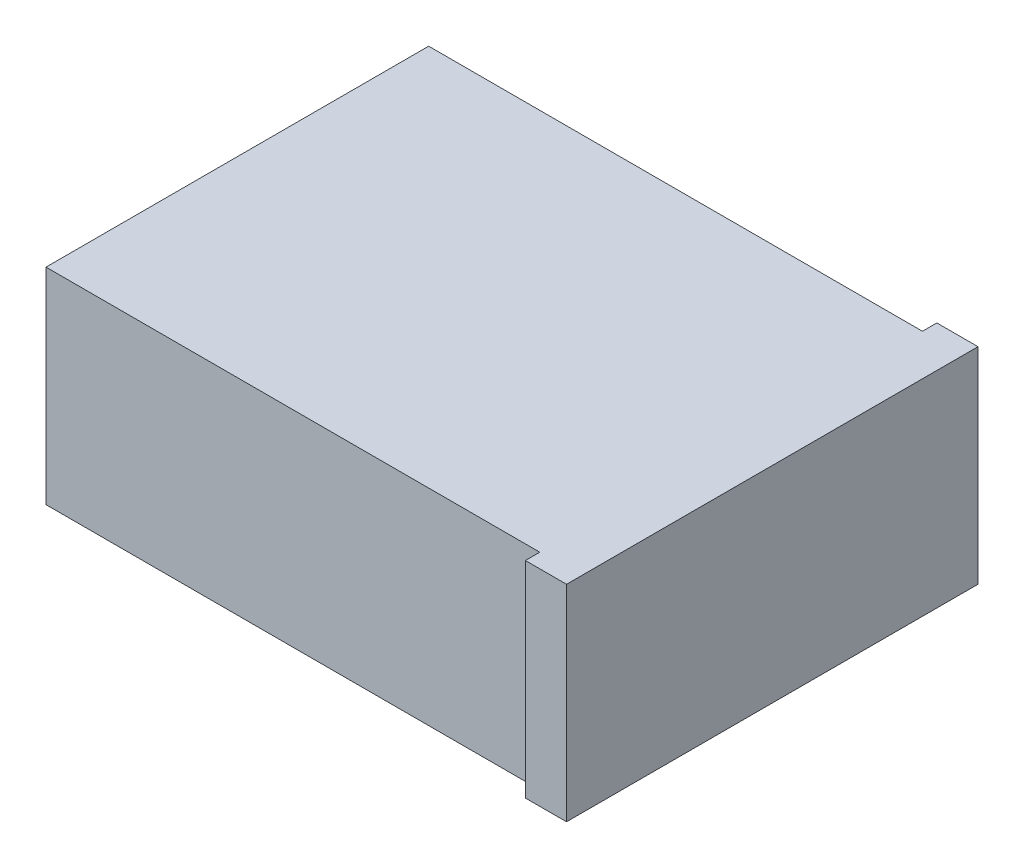
SolidWorks part; units mm, degrees
ref_plane "前视基准面" through (0, 0, 0) normal (0, 0, 1) x (1, 0, 0)
ref_plane "上视基准面" through (0, 0, 0) normal (0, 1, 0) x (1, 0, 0)
ref_plane "右视基准面" through (0, 0, 0) normal (1, 0, 0) x (0, 0, -1)
sketch "草图1" plane through (0, 0, 0) normal (0, 1, 0) x (1, 0, 0)
  line L0 (65, 50) -> (65, -50)
  line L1 (-65, 46.5) -> (55, 46.5)
  line L2 (-65, 46.5) -> (-65, -46.5)
  line L3 (-65, -46.5) -> (55, -46.5)
  line L4 (65, 46.5) -> (65, -46.5)
  line L5 (-65, 46.5) -> (65, -46.5) construction
  line L6 (-65, -46.5) -> (65, 46.5) construction
  line L7 (55, -50) -> (65, -50)
  line L8 (55, -50) -> (55, -46.5)
  line L9 (55, 50) -> (65, 50)
  line L11 (55, -50) -> (75, 50) construction
  line L12 (55, 50) -> (75, -50) construction
  line L13 (55, 46.5) -> (55, 50)
  point P0 (0, 0)
  point P6 (65, 0)
  dimension "D1" = 130
  dimension "D2" = 93
extrude "凸台-拉伸1" add sketch "草图1" along normal blind 50 contours L13 L1 L2 L3 L8 L7 L0 L9
